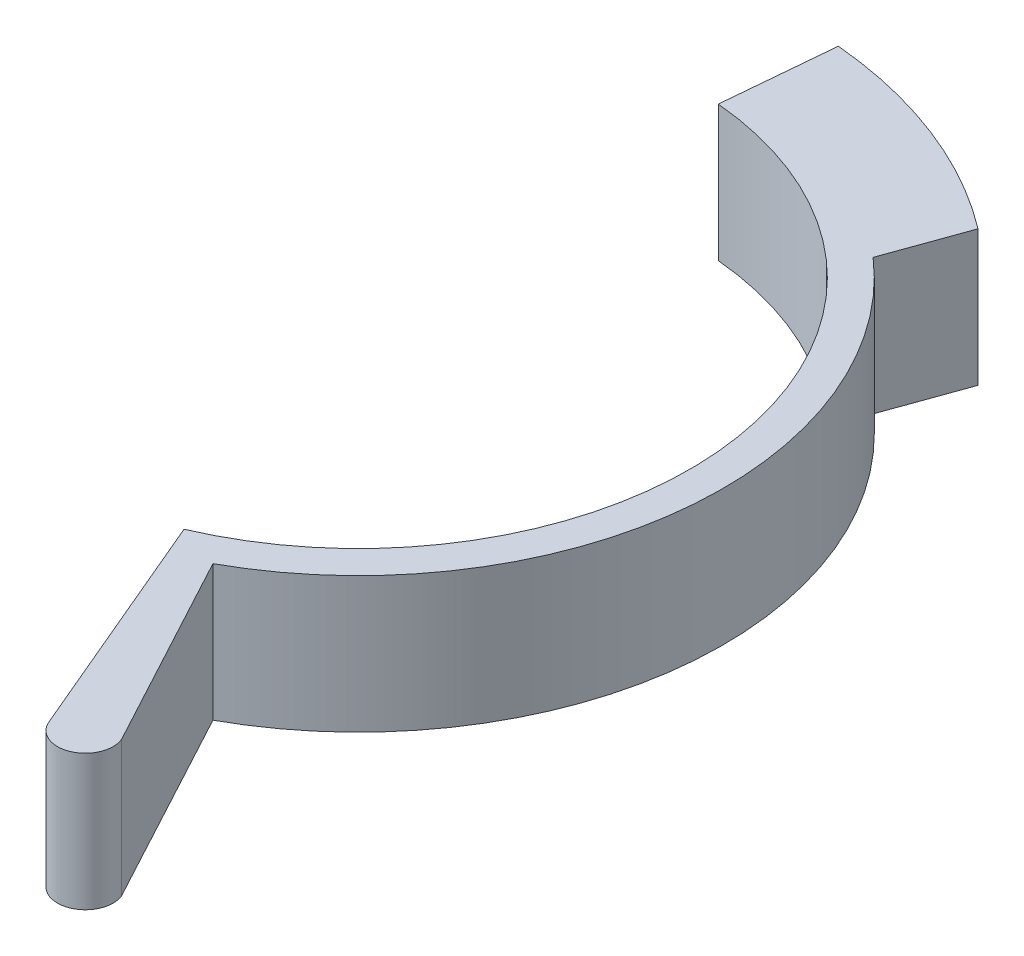
SolidWorks part; units mm, degrees
ref_plane "Plano frontal" through (0, 0, 0) normal (0, 0, 1) x (1, 0, 0)
ref_plane "Plano superior" through (0, 0, 0) normal (0, 1, 0) x (1, 0, 0)
ref_plane "Plano direito" through (0, 0, 0) normal (1, 0, 0) x (0, 0, -1)
sketch "Esboço1" plane through (0, 0, 0) normal (0, 1, 0) x (1, 0, 0)
  line L0 (21.6845, 24.8682) -> (24.1939, 31.8537)
  line L2 (12.9939, -30.3341) -> (11.8236, -27.5718)
  line L4 (0, 0) -> (0, -30) construction
  line L5 (0, 0) -> (5.8657, 32.4745) construction
  line L6 (3, -40) -> (2.9916, -39.888)
  line L7 (3.5787, 39.8396) -> (2.6841, 29.8797)
  line L13 (12.9939, -30.3341) -> (20.7957, -48.7497)
  line L17 (15.7246, -36.7796) -> (14.5543, -34.0173) construction
  line L19 (25.4536, -46.854) -> (15.8233, -28.959)
  arc A2 (11.8236, -27.5718) -> (2.6841, 29.8797) centre (0, 0) ccw
  arc A11 (24.1939, 31.8537) -> (3.5787, 39.8396) centre (0, 0) ccw
  arc A18 (15.8233, -28.959) -> (21.6864, 24.8737) centre (0, 0) ccw
  arc A20 (20.7957, -48.7497) -> (25.1986, -46.3802) centre (23.1246, -47.8018) ccw
  arc A21 (27.8629, -17.6821) -> (21.6864, 24.8737) centre (0, 0) ccw
  arc A22 (27.8629, -17.6821) -> (21.6864, 24.8737) centre (0, 0) ccw
  arc A25 (15.8233, -28.959) -> (26.071, -20.2312) centre (0, 0) ccw
  arc A26 (15.8233, -28.959) -> (26.071, -20.2312) centre (0, 0) ccw
  dimension "D1" = 5
  dimension "D2" = 20
  dimension "D3" = 30
extrude "Ressalto-extrusão1" add sketch "Esboço1" along normal blind 12.26
ref_plane "Plano1" through (0, 12.26, 0) normal (0, 1, 0) x (1, 0, 0)
